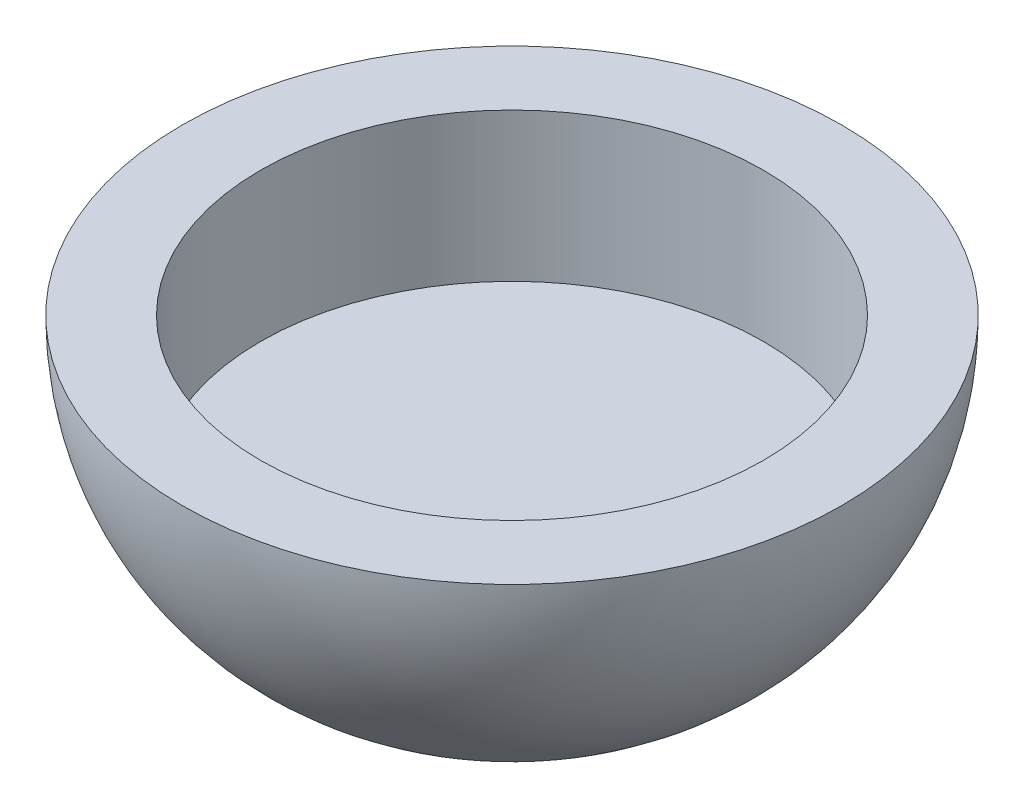
SolidWorks part; units mm, degrees
ref_plane "Front Plane" through (0, 0, 0) normal (0, 0, 1) x (1, 0, 0)
ref_plane "Top Plane" through (0, 0, 0) normal (0, 1, 0) x (1, 0, 0)
ref_plane "Right Plane" through (0, 0, 0) normal (1, 0, 0) x (0, 0, -1)
sketch "Sketch1" plane through (0, 0, 0) normal (0, 0, 1) x (1, 0, 0)
  line L0 (0, 0) -> (0, 9) construction
  line L1 (0, 9) -> (10, 9)
  line L2 (1, 0) -> (0, 0)
  line L3 (0, 0) -> (0, 9)
  arc A0 (10, 9) -> (1, 0) centre (1, 9) cw
  dimension "D1" = 10
  dimension "D2" = 9
revolve "Revolve2" add sketch "Sketch1" angle 360 about L0
sketch "Sketch2" plane through (0, 9, 0) normal (0, 1, 0) x (1, 0, 0)
  circle A0 centre (0, 0) radius 7.625
  dimension "D1" = 15.25
extrude "Cut-Extrude1" cut sketch "Sketch2" against normal blind 4.5 contours A0
